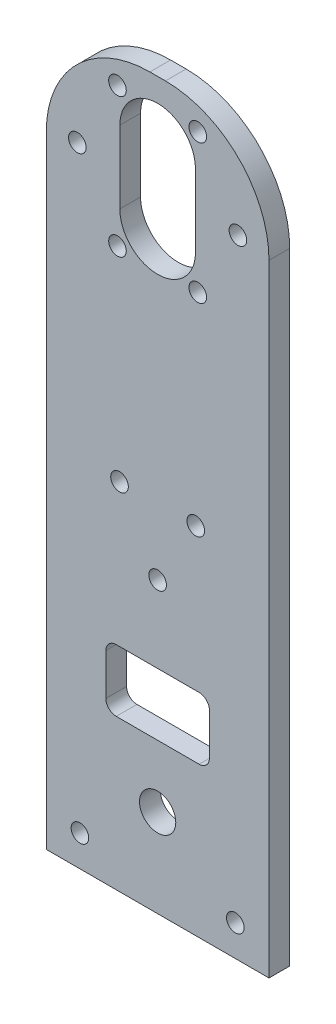
SolidWorks part; units mm, degrees
ref_plane "Front Plane" through (0, 0, 0) normal (0, 0, 1) x (1, 0, 0)
ref_plane "Top Plane" through (0, 0, 0) normal (0, 1, 0) x (1, 0, 0)
ref_plane "Right Plane" through (0, 0, 0) normal (1, 0, 0) x (0, 0, -1)
sketch "Sketch1" plane through (0, 0, 0) normal (0, 0, 1) x (1, 0, 0)
  line L0 (20.5, -120.2) -> (20.5, 19.8)
  line L1 (20.5, 19.8) -> (-22.5, 19.8)
  line L2 (-22.5, 19.8) -> (-22.5, -120.2)
  line L3 (-1, 8) -> (-1, -6) construction
  line L4 (-1, 14.6) -> (-1, -162.3914) construction
  line L5 (20.5, -120.2) -> (-22.5, -120.2)
  line L6 (6.3, 8) -> (6.3, -6)
  line L7 (-8.3, 8) -> (-8.3, -6)
  line L8 (-7.6, -6) -> (-7.6, 8) construction
  line L9 (20.5, -19.8) -> (-22.5, -19.8) construction
  line L11 (-9, -91.2) -> (7, -91.2)
  line L12 (-11, -89.2) -> (-11, -81.2)
  line L13 (-9, -79.2) -> (7, -79.2)
  line L14 (9, -89.2) -> (9, -81.2)
  line L15 (-11, -91.2) -> (9, -79.2) construction
  line L16 (-11, -79.2) -> (9, -91.2) construction
  arc A0 (17.796, 1.3878) -> (-19.796, 1.3878) centre (-1, 1) ccw construction
  circle A1 centre (6.7485, -12.4259) radius 1.7
  circle A2 centre (-8.7544, -12.4259) radius 1.7
  circle A3 centre (-16.5058, 1) radius 1.7
  circle A4 centre (-8.7544, 14.4259) radius 1.7
  circle A5 centre (6.7485, 14.4259) radius 1.7
  circle A6 centre (14.5, 1) radius 1.7
  circle A7 centre (14, -114.2) radius 1.7
  circle A8 centre (-16, -114.2) radius 1.7
  arc A9 (6.3, 8) -> (-8.3, 8) centre (-1, 8) ccw
  arc A10 (-8.3, -6) -> (6.3, -6) centre (-1, -6) ccw
  arc A11 (9, -89.2) -> (7, -91.2) centre (7, -89.2) cw
  arc A12 (-11, -89.2) -> (-9, -91.2) centre (-9, -89.2) ccw
  arc A13 (-7.6, -6) -> (5.6, -6) centre (-1, -6) ccw construction
  arc A14 (-1, 14.6) -> (-7.6, 8) centre (-1, 8) ccw construction
  arc A15 (-11, -81.2) -> (-9, -79.2) centre (-9, -81.2) cw
  arc A16 (7, -79.2) -> (9, -81.2) centre (7, -81.2) cw
  circle A17 centre (-1, -103.2) radius 3.5
  point P34 (-1, 1)
  point P51 (-1, -85.2)
  dimension "D3" = 3.4
  dimension "D4" = 6
  dimension "D5" = 15
  dimension "D8" = 2
  dimension "D10" = 7
  dimension "D1" = 20
  dimension "D2" = 140
  dimension "D6" = 0.7
  dimension "D7" = 12
  dimension "D9" = 35
  dimension "D11" = 12
extrude "Boss-Extrude1" add sketch "Sketch1" along normal blind 4
fillet "Fillet1" radius 20 2 edges at (-22.5, 19.8, 2) (20.5, 19.8, 2)
sketch "Sketch2" plane through (0, 0, 4) normal (0, 0, 1) x (1, 0, 0)
  circle A0 centre (-1, -64.4017) radius 1.7
  circle A1 centre (6.3612, -51.6517) radius 1.7
  circle A2 centre (-8.3612, -51.6517) radius 1.7
extrude "dependant" cut sketch "Sketch2" against normal blind 10
equation "\"width\"= 50mm"
